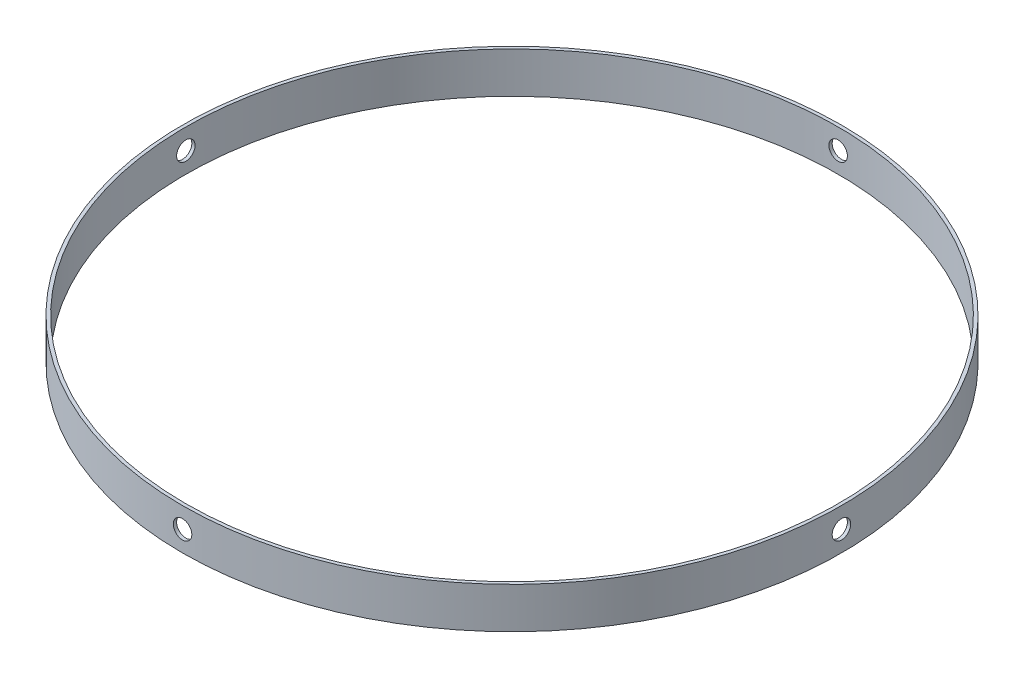
SolidWorks part; units mm, degrees
ref_plane "Front Plane" through (0, 0, 0) normal (0, 0, 1) x (1, 0, 0)
ref_plane "Top Plane" through (0, 0, 0) normal (0, 1, 0) x (1, 0, 0)
ref_plane "Right Plane" through (0, 0, 0) normal (1, 0, 0) x (0, 0, -1)
sketch "Sketch1" plane through (0, 0, 0) normal (0, 1, 0) x (1, 0, 0)
  circle A0 centre (0, 0) radius 79.5
  circle A1 centre (0, 0) radius 80.3
  dimension "D1" = 159
  dimension "D2" = 0.8
extrude "Boss-Extrude1" add sketch "Sketch1" along normal mid plane 10 contours A1 A0
sketch "Sketch2" plane through (0, 0, 0) normal (0, 0, 1) x (1, 0, 0)
  circle A0 centre (0, 0) radius 2.25
  dimension "D1" = 4.5
extrude "Cut-Extrude3" cut sketch "Sketch2" against normal through all contours A0
pattern_circular "CirPattern1" count 4 every 90 about axis through (0, 5, 0) along (0, -1, 0) of "Cut-Extrude3"
equation "\"diameter\"=0.177165"
equation "\"D1@Sketch2\"=\"diameter\""
